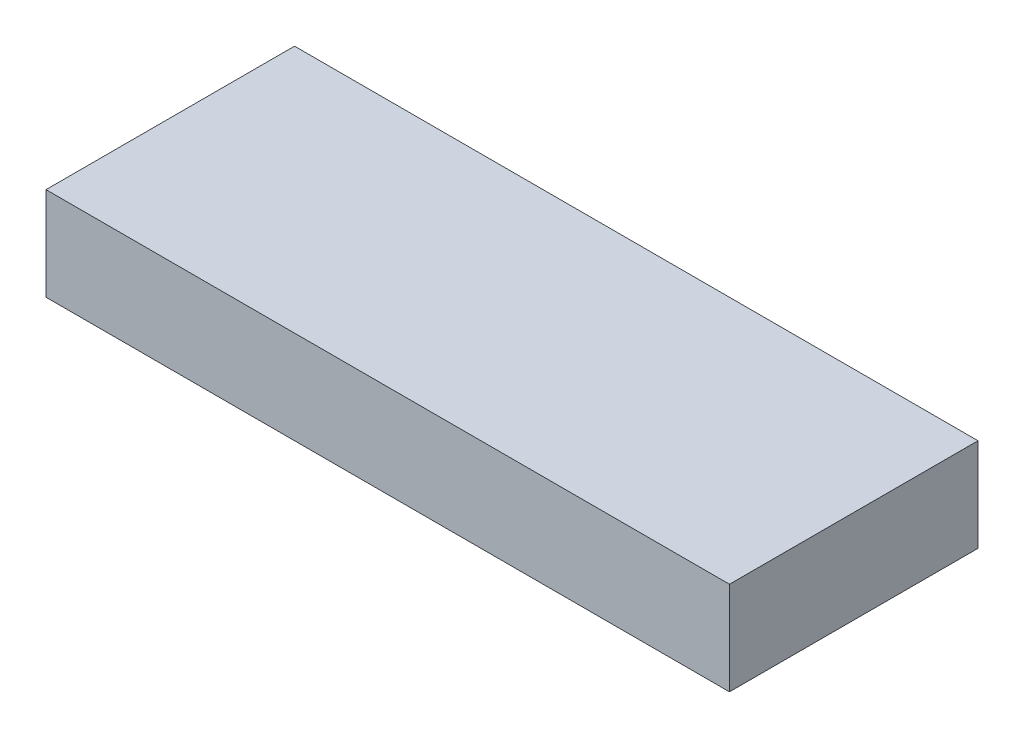
SolidWorks part; units mm, degrees
ref_plane "前视基准面" through (0, 0, 0) normal (0, 0, 1) x (1, 0, 0)
ref_plane "上视基准面" through (0, 0, 0) normal (0, 1, 0) x (1, 0, 0)
ref_plane "右视基准面" through (0, 0, 0) normal (1, 0, 0) x (0, 0, -1)
sketch "草图1" plane through (0, 0, 0) normal (0, 1, 0) x (1, 0, 0)
  line L1 (1100, -400) -> (-1100, -400)
  line L2 (1100, -400) -> (1100, 400)
  line L3 (1100, 400) -> (-1100, 400)
  line L4 (-1100, -400) -> (-1100, 400)
  line L5 (1100, -400) -> (-1100, 400) construction
  line L6 (1100, 400) -> (-1100, -400) construction
  point P0 (0, 0)
  dimension "D1" = 2200
  dimension "D2" = 800
extrude "凸台-拉伸1" add sketch "草图1" along normal blind 300
